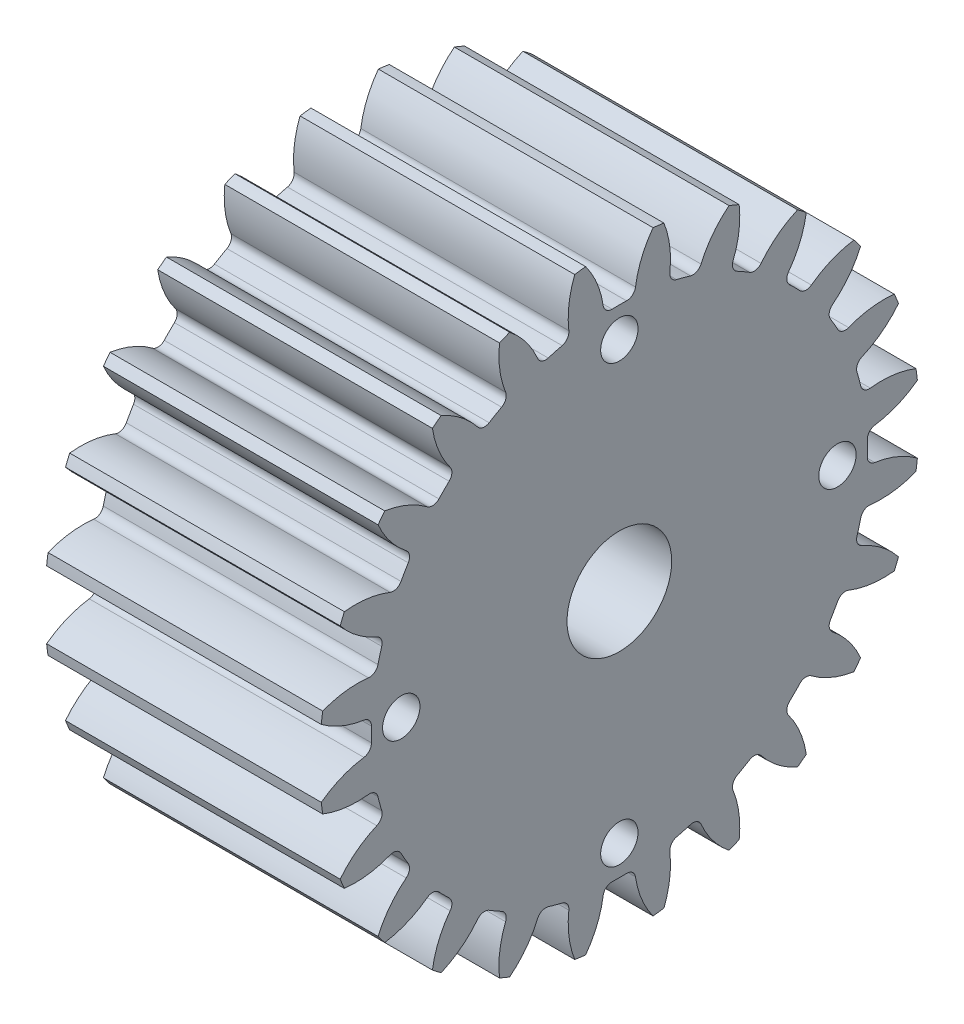
SolidWorks part; units mm, degrees
ref_plane "Front Plane" through (0, 0, 0) normal (0, 0, 1) x (1, 0, 0)
ref_plane "Top Plane" through (0, 0, 0) normal (0, 1, 0) x (1, 0, 0)
ref_plane "Right Plane" through (0, 0, 0) normal (1, 0, 0) x (0, 0, -1)
sketch "Sketch1" plane through (0, 0, 0) normal (1, 0, 0) x (0, 0, -1)
  circle A0 centre (0, 0) radius 4.7625
  circle A1 centre (0, 0) radius 27.3
  dimension "D1" = 9.525
  dimension "D2" = 54.6
extrude "Boss-Extrude2" add sketch "Sketch1" along normal blind 25
sketch "Sketch3" plane through (25, 0, 0) normal (1, 0, 0) x (0, 0, -1)
  line L0 (0, 0) -> (0, 27.3) construction
  line L1 (-1.3953, 22.5318) -> (0, 0) construction
  line L2 (0, 19.7321) -> (-0.8252, 21.9993) construction
  circle A0 centre (0, 0) radius 27.3 construction
  arc A1 (1.3953, 22.5318) -> (-1.3953, 22.5318) centre (0, 0) ccw
  arc A2 (1.9643, 25.1233) -> (-1.9643, 25.1233) centre (0, 0) ccw construction
  arc A3 (3.0678, 27.1271) -> (-3.0678, 27.1271) centre (0, 0) ccw
  arc A4 (-3.0678, 27.1271) -> (-1.3953, 22.5318) centre (-10.0098, 21.9984) cw
  arc A5 (3.0678, 27.1271) -> (1.3953, 22.5318) centre (10.0098, 21.9984) ccw
  point P17 (-1.8993, 24.9504)
  dimension "D1" = 54.6
  dimension "D2" = 50.4
  dimension "D3" = 4.725
  dimension "D4" = 20
  dimension "D5" = 3.9287
extrude "Cut-Extrude1" cut sketch "Sketch3" against normal through all
fillet "Fillet1" radius 0.798 2 edges at (12.5, 22.5318, -1.3953) (12.5, 22.5318, 1.3953)
pattern_circular "CirPattern2" count 24 over 360 about axis through (0, 0, 0) along (1, 0, 0) of "Fillet1", "Cut-Extrude1"
sketch "Sketch4" plane through (25, 0, 0) normal (1, 0, 0) x (0, 0, -1)
  circle A0 centre (0, 0) radius 19.8501 construction
  circle A1 centre (0, 19.8501) radius 1.7
  circle A2 centre (19.8501, 0) radius 1.7
  circle A3 centre (0, -19.8501) radius 1.7
  circle A4 centre (-19.8501, 0) radius 1.7
  point P14 (0, 0)
  dimension "D1" = 19.8501
  dimension "D2" = 3.4
  dimension "D3" = 4
extrude "Cut-Extrude2" cut sketch "Sketch4" against normal blind 10
sketch "Sketch5" plane through (25, 0, 0) normal (1, 0, 0) x (0, 0, -1)
  point P0 (0, 0)
equation "\"No of teeth\"= 24"
equation "\"Module\"= 2.1"
equation "\"Outer Diameter\"= ( \"No of teeth\" + 2 ) * \"Module\""
equation "\"Pitch Diameter\"= \"No of teeth\" * \"Module\""
equation "\"Backlash\"= 0.3 * \"Module\""
equation "\"Arc Length\"= ( ( \"Module\" * pi ) / 2 ) + \"Backlash\""
equation "\"Fillet Radius\"= 0.38 * \"Module\""
equation "\"Bore Diameter\"= .375in"
equation "\"Presseure angle\"= 20"
equation "\"Tooth Depth\"= IIF ( \"Module\" <= 1.25 , 2.4 * \"Module\" , 2.25 * \"Module\" )"
equation "\"D1@Sketch1\"=\"Bore Diameter\""
equation "\"D2@Sketch1\"=\"Outer Diameter\""
equation "\"D1@Sketch3\"=\"Outer Diameter\""
equation "\"D2@Sketch3\"=\"Pitch Diameter\""
equation "\"D3@Sketch3\"=\"Tooth Depth\""
equation "\"D4@Sketch3\"=\"Presseure angle\""
equation "\"D5@Sketch3\"=\"Arc Length\""
equation "\"D1@Fillet1\"=\"Fillet Radius\""
equation "\"D1@CirPattern2\"=\"No of teeth\""
